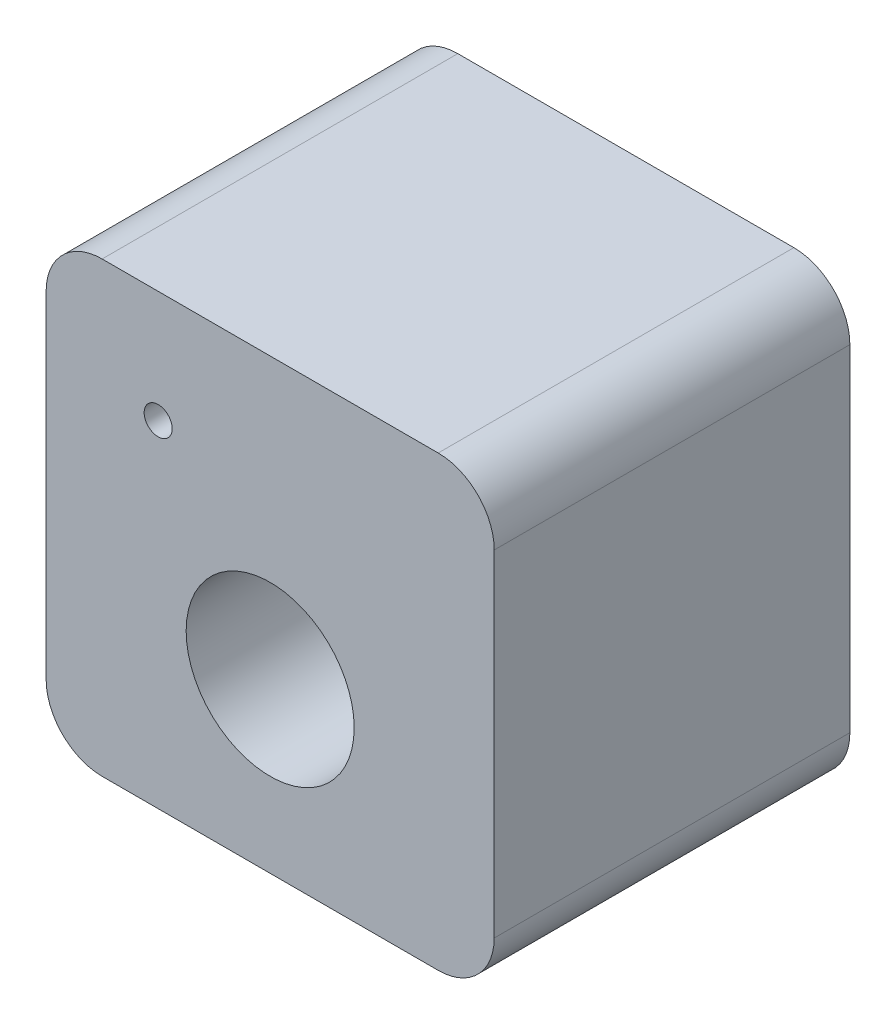
SolidWorks part; units mm, degrees
material "Balsa"
ref_plane "Front Plane" through (0, 0, 0) normal (0, 0, 1) x (1, 0, 0)
ref_plane "Top Plane" through (0, 0, 0) normal (0, 1, 0) x (1, 0, 0)
ref_plane "Right Plane" through (0, 0, 0) normal (1, 0, 0) x (0, 0, -1)
sketch "Sketch1" plane through (0, 0, 0) normal (0, 0, 1) x (1, 0, 0)
  line L0 (4, 3) -> (4, 0) construction
  line L1 (0, 0) -> (8, 0)
  line L2 (0, 0) -> (0, 8)
  line L3 (0, 8) -> (8, 8)
  line L4 (8, 0) -> (8, 8)
  circle A0 centre (4, 3) radius 1.5
  circle A1 centre (2, 6) radius 0.25
  dimension "D3" = 3
  dimension "D4" = 3
  dimension "D5" = 2
  dimension "D6" = 2
  dimension "D7" = 0.5
  dimension "D1" = 8
  dimension "D2" = 8
extrude "Boss-Extrude1" add sketch "Sketch1" along normal blind 6.35
fillet "Fillet1" radius 1 4 edges at (0, 0, 3.175) (8, 0, 3.175) (8, 8, 3.175) (0, 8, 3.175)
